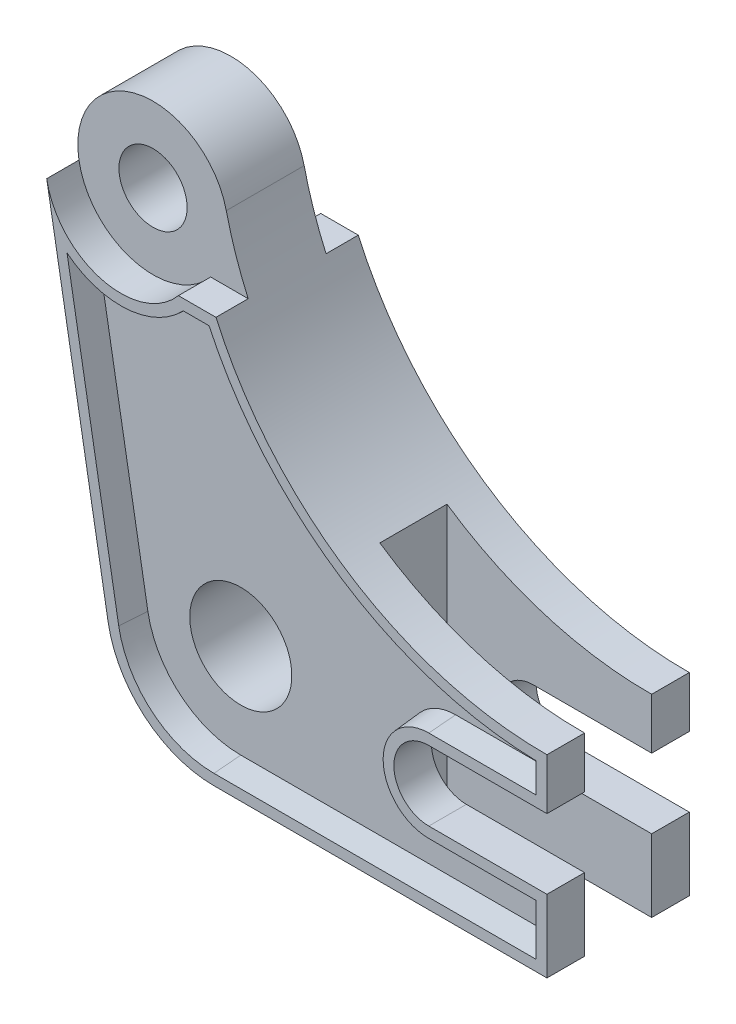
SolidWorks part; units mm, degrees
material "AISI 1020 Steel, Cold Rolled"
ref_plane "Front Plane" through (0, 0, 0) normal (0, 0, 1) x (1, 0, 0)
ref_plane "Top Plane" through (0, 0, 0) normal (0, 1, 0) x (1, 0, 0)
ref_plane "Right Plane" through (0, 0, 0) normal (1, 0, 0) x (0, 0, -1)
sketch "Sketch2" plane through (0, 0, 0) normal (0, 0, 1) x (1, 0, 0)
  line L0 (0, 0) -> (-62, 0)
  line L1 (-62, 20) -> (-79.3409, 84.717) construction
  line L2 (-62, 20) -> (-62, 0) construction
  line L3 (-81.7045, 16.5744) -> (-93.134, 82.3191)
  line L4 (0, 0) -> (0, 13.5)
  line L5 (0, 13.5) -> (-22, 13.5)
  line L6 (-22, 26.5) -> (0, 26.5)
  line L7 (0, 26.5) -> (0, 36)
  arc A0 (-81.7045, 16.5744) -> (-62, 0) centre (-62, 20) ccw
  circle A1 centre (-79.3409, 84.717) radius 6.35
  arc A2 (-65.7021, 87.8768) -> (-93.134, 82.3191) centre (-79.3409, 84.717) ccw
  circle A3 centre (-62, 20) radius 9.5
  arc A4 (-22, 26.5) -> (-22, 13.5) centre (-22, 20) ccw
  arc A5 (-65.7021, 87.8768) -> (0, 36) centre (-0.4309, 102.9986) ccw
  dimension "D2" = 40
  dimension "D3" = 67
  dimension "D4" = 15
  dimension "D5" = 12.7
  dimension "D6" = 28
  dimension "D8" = 19
  dimension "D9" = 13
  dimension "D10" = 22
  dimension "D12" = 36
  dimension "D13" = 134
  dimension "D1" = 62
  dimension "D7" = 14
  dimension "D11" = 20
extrude "Boss-Extrude2" add sketch "Sketch2" along normal blind 26.5
sketch "Sketch3" plane through (0, 0, 26.5) normal (0, 0, 1) x (1, 0, 0)
  line L0 (-68.6171, 75.717) -> (-61.625, 75.717)
  arc A0 (-65.7021, 87.8768) -> (-68.6171, 75.717) centre (-79.3409, 84.717) ccw
  arc A1 (-65.7021, 87.8768) -> (0, 36) centre (-0.4309, 102.9986) ccw construction
  arc A2 (-65.7021, 87.8768) -> (-61.625, 75.717) centre (-0.4309, 102.9986) ccw
  dimension "D1" = 28
  dimension "D2" = 9
extrude "Cut-Extrude1" cut sketch "Sketch3" against normal blind 6
sketch "Sketch4" plane through (0, 0, 0) normal (0, 0, -1) x (-1, 0, 0)
  line L0 (68.6171, 75.717) -> (61.625, 75.717)
  arc A0 (68.6171, 75.717) -> (65.7021, 87.8768) centre (79.3409, 84.717) ccw
  arc A1 (0, 36) -> (65.7021, 87.8768) centre (0.4309, 102.9986) ccw construction
  arc A2 (61.625, 75.717) -> (65.7021, 87.8768) centre (0.4309, 102.9986) ccw
  dimension "D1" = 28
  dimension "D2" = 9
  dimension "D3" = 9
extrude "Cut-Extrude2" cut sketch "Sketch4" against normal blind 6
ref_plane "Plane1" through (0, 0, 13.25) normal (0, 0, 1) x (1, 0, 0)
sketch "Sketch6" plane through (0, 0, 13.25) normal (0, 0, 1) x (1, 0, 0)
  line L0 (0, 0) -> (-38.1088, 0)
  line L1 (-62, 0) -> (0, 0) construction
  line L2 (-38.1088, 0) -> (-38.1088, 47.5967)
  line L3 (0, 0) -> (0, 36)
  arc A0 (-61.625, 75.717) -> (0, 36) centre (-0.4309, 102.9986) ccw construction
  arc A1 (-38.1088, 47.5967) -> (0, 36) centre (-0.4309, 102.9986) ccw
extrude "Cut-Extrude3" cut sketch "Sketch6" against normal blind 6.25 and the other way blind 6.25
sketch "Sketch7" plane through (0, 0, 26.5) normal (0, 0, 1) x (1, 0, 0)
  line L0 (-89.3509, 72.2351) -> (-79.734, 16.917)
  line L1 (-62.9096, 73.717) -> (-67.7219, 73.717)
  line L2 (-2, 28.5) -> (-2, 34.0165)
  line L3 (-22, 28.5) -> (-2, 28.5)
  line L4 (-2, 11.5) -> (-22, 11.5)
  line L5 (-2, 2) -> (-2, 11.5)
  line L6 (-2, 2) -> (-62, 2)
  line L14 (0, 0) -> (-62, 0)
  line L15 (0, 0) -> (0, 13.5)
  line L16 (0, 13.5) -> (-22, 13.5)
  line L17 (-22, 26.5) -> (0, 26.5)
  line L18 (0, 26.5) -> (0, 36)
  line L19 (-61.625, 75.717) -> (-68.6171, 75.717)
  line L20 (-93.134, 82.3191) -> (-81.7045, 16.5744)
  arc A0 (-62, 2) -> (-79.734, 16.917) centre (-62, 20) cw
  arc A1 (-67.7219, 73.717) -> (-89.3509, 72.2351) centre (-79.3409, 84.717) cw
  arc A2 (-2, 34.0165) -> (-62.9096, 73.717) centre (-0.4309, 102.9986) cw
  arc A3 (-22, 11.5) -> (-22, 28.5) centre (-22, 20) cw
  arc A8 (-22, 13.5) -> (-22, 26.5) centre (-22, 20) cw
  arc A11 (-68.6171, 75.717) -> (-93.134, 82.3191) centre (-79.3409, 84.717) cw
  arc A12 (0, 36) -> (-61.625, 75.717) centre (-0.4309, 102.9986) cw
  arc A13 (-62, 0) -> (-81.7045, 16.5744) centre (-62, 20) cw
  dimension "D1" = 67
  dimension "D2" = 14
  dimension "D3" = 2
extrude "Cut-Extrude7" cut sketch "Sketch7" against normal blind 5 draft 5 contours A0 L0 A1 L1 A2 L2 L3 A3 L4 L5 L6
equation "\"A\"= 62mm"
equation "\"B\"= 20mm"
equation "\"C\"= 26.5mm"
